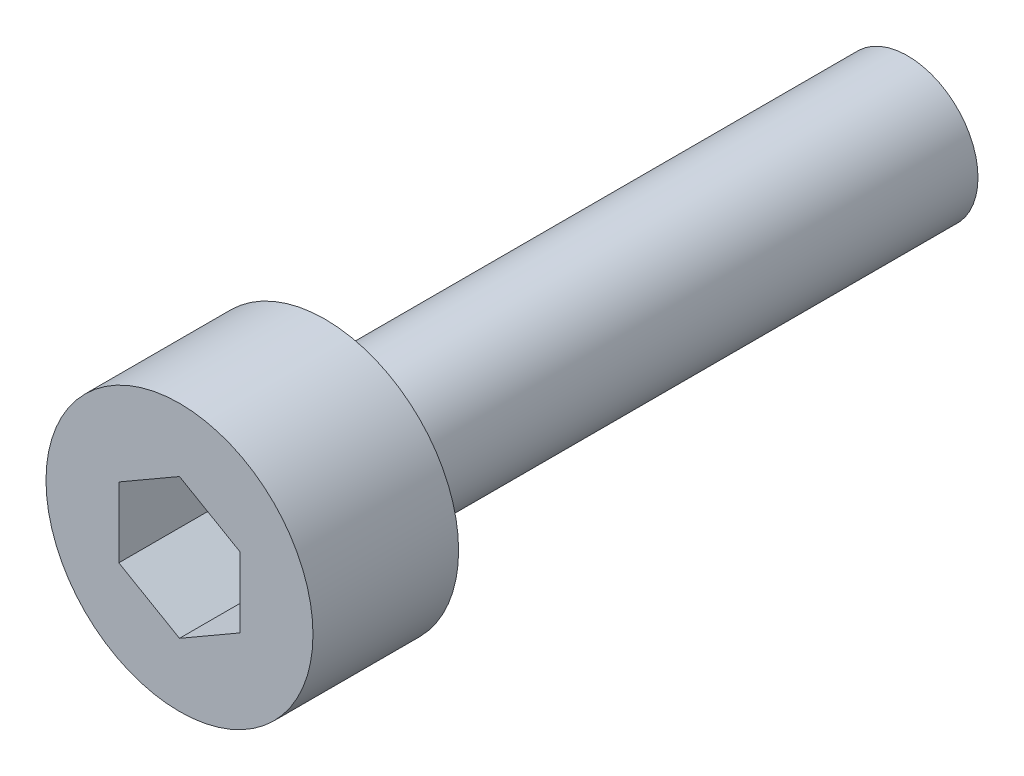
SolidWorks part; units mm, degrees
ref_plane "前视基准面" through (0, 0, 0) normal (0, 0, 1) x (1, 0, 0)
ref_plane "上视基准面" through (0, 0, 0) normal (0, 1, 0) x (1, 0, 0)
ref_plane "右视基准面" through (0, 0, 0) normal (1, 0, 0) x (0, 0, -1)
other "Configuration Table"
sketch "草图1" plane through (0, 0, 0) normal (0, 0, 1) x (1, 0, 0)
  circle A0 centre (0, 0) radius 1.45
extrude "Shank_threads_simplified" add sketch "草图1" against normal blind 12
sketch "草图2" plane through (0, 0, 0) normal (0, 0, 1) x (1, 0, 0)
  circle A0 centre (0, 0) radius 2.75
extrude "Head" add sketch "草图2" along normal blind 3
ref_plane "Plane_z_3_2" through (0, 0, 3) normal (0, 0, 1) x (1, 0, 0)
sketch "草图3" plane through (0, 0, 3) normal (0, 0, 1) x (1, 0, 0)
  line L0 (1.25, 0.7217) -> (0, 1.4434)
  line L1 (0, 1.4434) -> (-1.25, 0.7217)
  line L2 (-1.25, 0.7217) -> (-1.25, -0.7217)
  line L3 (-1.25, -0.7217) -> (0, -1.4434)
  line L4 (0, -1.4434) -> (1.25, -0.7217)
  line L5 (1.25, -0.7217) -> (1.25, 0.7217)
extrude "Hex_socket" cut sketch "草图3" against normal blind 1.95
